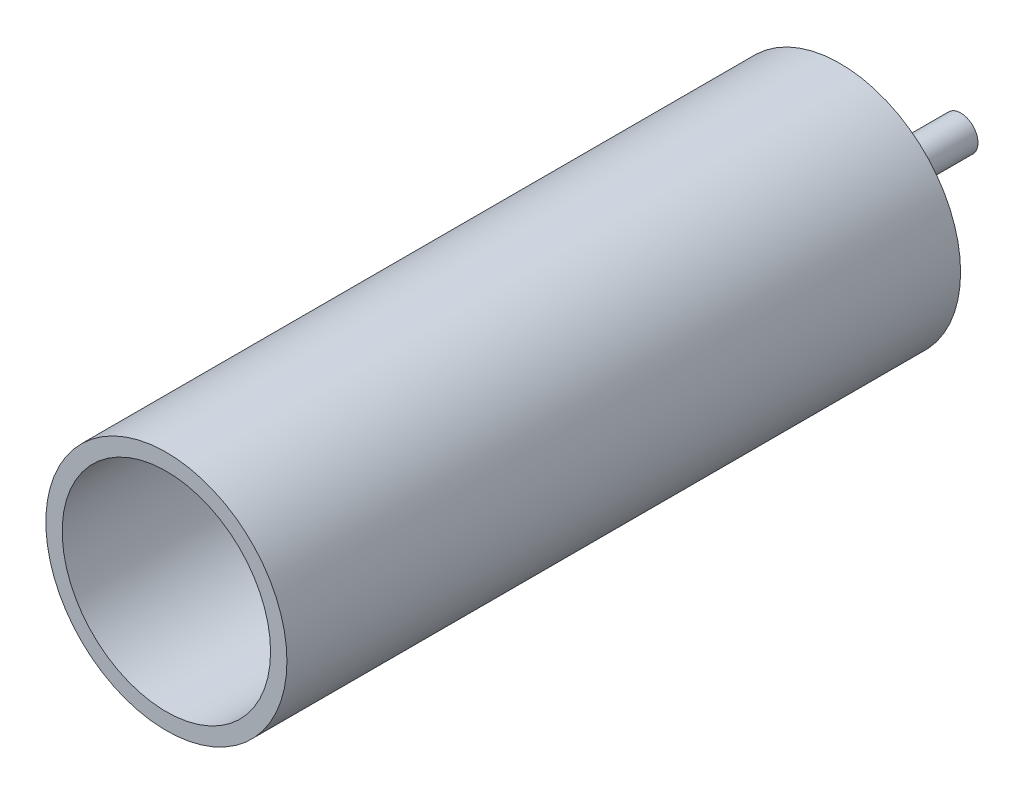
SolidWorks part; units mm, degrees
ref_plane "Front Plane" through (0, 0, 0) normal (0, 0, 1) x (1, 0, 0)
ref_plane "Top Plane" through (0, 0, 0) normal (0, 1, 0) x (1, 0, 0)
ref_plane "Right Plane" through (0, 0, 0) normal (1, 0, 0) x (0, 0, -1)
sketch "Sketch1" plane through (0, 0, 0) normal (0, 0, 1) x (1, 0, 0)
  circle A0 centre (0, 0) radius 35
  dimension "D1" = 70
extrude "Boss-Extrude1" add sketch "Sketch1" against normal blind 195.58
sketch "Sketch2" plane through (0, 0, -195.58) normal (0, 0, -1) x (-1, 0, 0)
  circle A0 centre (0, 0) radius 5
  dimension "D1" = 10
extrude "Boss-Extrude2" add sketch "Sketch2" along normal blind 35.052
sketch "Sketch5" plane through (0, 0, 0) normal (0, 0, 1) x (1, 0, 0)
  circle A0 centre (0, 0) radius 30.25
  dimension "D1" = 60.5
extrude "Cut-Extrude1" cut sketch "Sketch5" against normal blind 152.4
